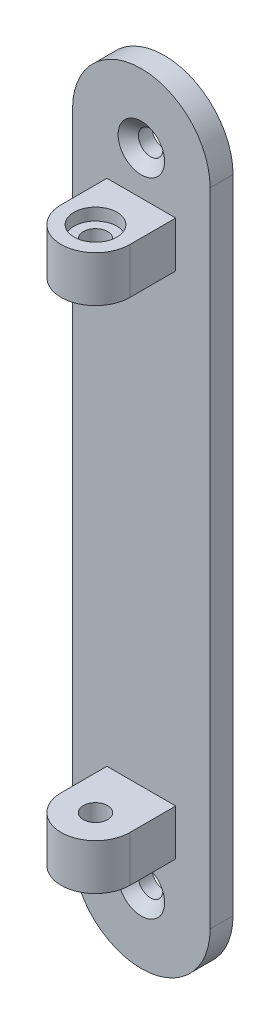
SolidWorks part; units mm, degrees
ref_plane "Front Plane" through (0, 0, 0) normal (0, 0, 1) x (1, 0, 0)
ref_plane "Top Plane" through (0, 0, 0) normal (0, 1, 0) x (1, 0, 0)
ref_plane "Right Plane" through (0, 0, 0) normal (1, 0, 0) x (0, 0, -1)
sketch "Sketch1" plane through (0, 0, 0) normal (0, 0, 1) x (1, 0, 0)
  line L0 (0, 0) -> (0, 88.9)
  line L1 (38.1, 88.9) -> (38.1, 0)
  line L2 (0, 0) -> (38.1, 0)
  arc A0 (0, 88.9) -> (38.1, 88.9) centre (19.05, 88.9) cw
  dimension "D2" = 19.05
  dimension "D1" = 88.9
extrude "Boss-Extrude1" add sketch "Sketch1" along normal blind 6.35
hole_wizard "CSK for 1/4 Flat Head Machine Screw (100)1" positions "Sketch4" profile "Sketch5" countersink size "1/4" standard "ANSI Inch" end condition through all
sketch "Sketch4" plane through (0, 0, 6.35) normal (0, 0, 1) x (1, 0, 0)
  arc A0 (38.1, 88.9) -> (0, 88.9) centre (19.05, 88.9) ccw construction
  point P0 (19.05, 88.9)
  point P3 (19.05, 88.9)
  point P6 (0, 0)
sketch "Sketch5" plane through (19.05, 88.9, 6.35) normal (1, 0, 0) x (0, -1, 0)
  line L0 (0, 0) -> (0, 6.35)
  line L1 (0, 6.35) -> (3.3782, 6.35)
  line L2 (3.3782, 6.35) -> (3.3782, 2.5682)
  line L3 (3.3782, 2.5682) -> (6.4389, 0)
  line L5 (6.4389, 0) -> (0, 0)
  line L6 (-3.3782, 2.5682) -> (-6.4389, 0) construction
  line L11 (0, -6.35) -> (0, 107.95) construction
  dimension "Thru Hole Dia." = 6.7564
  dimension "Thru Hole Depth" = 6.35
  dimension "Near C'Sink Dia." = 12.8778
  dimension "Near C'Sink Angle" = 100
sketch "Sketch6" plane through (0, 0, 6.35) normal (0, 0, 1) x (1, 0, 0)
  line L0 (19.05, 0) -> (19.05, 64.1693) construction
  line L1 (9.525, 76.8693) -> (28.575, 76.8693)
  line L2 (9.525, 76.8693) -> (9.525, 64.1693)
  line L3 (9.525, 64.1693) -> (28.575, 64.1693)
  line L4 (28.575, 76.8693) -> (28.575, 64.1693)
  line L5 (0, 0) -> (38.1, 0) construction
  dimension "D1" = 12.7
  dimension "D2" = 19.05
extrude "Boss-Extrude2" add sketch "Sketch6" along normal blind 12.7
sketch "Sketch10" plane through (0, 76.8693, 0) normal (0, 1, 0) x (1, 0, 0)
  line L0 (9.525, -19.05) -> (28.575, -19.05)
  arc A0 (9.525, -19.05) -> (28.575, -19.05) centre (19.05, -19.05) ccw
extrude "Boss-Extrude3" add sketch "Sketch10" against normal up to surface (12.7 mm away) up to face at (19.05, 64.1693, 12.7)
hole_wizard "CBORE for 1/4 Button Head Cap Screw1" positions "Sketch11" profile "Sketch13" counterbore size "1/4" standard "ANSI Inch"
sketch "Sketch11" plane through (0, 76.8693, 0) normal (0, 1, 0) x (1, 0, 0)
  arc A0 (9.525, -19.05) -> (28.575, -19.05) centre (19.05, -19.05) ccw construction
  point P0 (19.05, -19.05)
  point P4 (0, 0)
sketch "Sketch13" plane through (19.05, 76.8693, 19.05) normal (1, 0, 0) x (0, 0, 1)
  line L0 (0, 0) -> (0, 14.7288)
  line L1 (0, 14.7288) -> (3.3782, 12.699)
  line L2 (3.3782, 12.699) -> (3.3782, 3.3528)
  line L3 (3.3782, 3.3528) -> (5.9538, 3.3528)
  line L4 (5.9538, 3.3528) -> (5.9538, 0)
  line L5 (5.9538, 0) -> (0, 0)
  line L10 (0, 14.7288) -> (-3.3782, 12.699) construction
  line L11 (0, -6.35) -> (0, 107.95) construction
  dimension "Hole Dia." = 6.7564
  dimension "Hole Depth" = 12.699
  dimension "C'Bore Dia." = 11.9075
  dimension "C'Bore Depth" = 3.3528
  dimension "Drill Angle" = 118
mirror "Mirror1" about plane through (0, 0, 6.35) normal (0, 1, 0) of bodies 105
